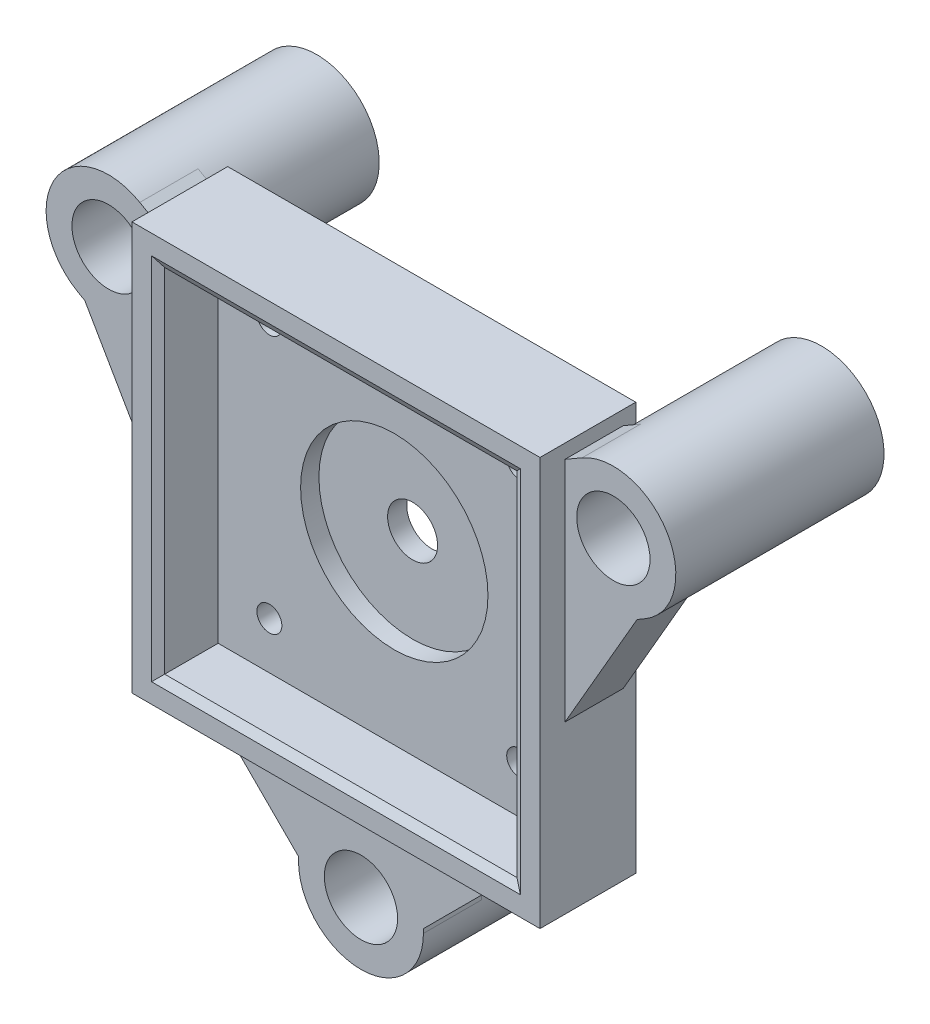
SolidWorks part; units mm, degrees
ref_plane "Ebene vorne" through (0, 0, 0) normal (0, 0, 1) x (1, 0, 0)
ref_plane "Ebene oben" through (0, 0, 0) normal (0, 1, 0) x (1, 0, 0)
ref_plane "Ebene rechts" through (0, 0, 0) normal (1, 0, 0) x (0, 0, -1)
sketch "Skizze1" plane through (0, 0, 0) normal (0, 0, 1) x (1, 0, 0)
  line L1 (-24.5, 24.5) -> (24.5, 24.5)
  line L2 (-24.5, 24.5) -> (-24.5, -24.5)
  line L3 (-24.5, -24.5) -> (24.5, -24.5)
  line L4 (24.5, 24.5) -> (24.5, -24.5)
  line L5 (-24.5, 24.5) -> (24.5, -24.5) construction
  line L6 (-24.5, -24.5) -> (24.5, 24.5) construction
  point P0 (0, 0)
  dimension "D1" = 49
  dimension "D2" = 49
extrude "Aufsatz-Linear austragen1" add sketch "Skizze1" along normal blind 11.5
sketch "Skizze2" plane through (0, 0, 11.5) normal (0, 0, 1) x (1, 0, 0)
  line L1 (-21.15, 21.15) -> (21.15, 21.15)
  line L2 (-21.15, 21.15) -> (-21.15, -21.15)
  line L3 (-21.15, -21.15) -> (21.15, -21.15)
  line L4 (21.15, 21.15) -> (21.15, -21.15)
  line L5 (-21.15, 21.15) -> (21.15, -21.15) construction
  line L6 (-21.15, -21.15) -> (21.15, 21.15) construction
  point P0 (0, 0)
  dimension "D1" = 42.3
  dimension "D2" = 42.3
extrude "Schnitt-Linear austragen1" cut sketch "Skizze2" against normal blind 5
sketch "Skizze3" plane through (0, 0, 6.5) normal (0, 0, 1) x (1, 0, 0)
  circle A0 centre (0, 0) radius 2.85
  dimension "D1" = 5.7
extrude "Schnitt-Linear austragen2" cut sketch "Skizze3" against normal blind 7
sketch "Skizze4" plane through (0, 0, 6.5) normal (0, 0, 1) x (1, 0, 0)
  circle A0 centre (0, 0) radius 35
sketch "Skizze5" plane through (0, 0, 6.5) normal (0, 0, 1) x (1, 0, 0)
  line L0 (0, -35) -> (0, 0) construction
  line L1 (-7.5, -35) -> (-7.5, 0)
  line L2 (7.5, -35) -> (7.5, 0)
  line L3 (30.3109, 17.5) -> (0, 0) construction
  line L4 (34.0609, 11.0048) -> (3.75, -6.4952)
  line L5 (26.5609, 23.9952) -> (-3.75, 6.4952)
  line L6 (-30.3109, 17.5) -> (0, 0) construction
  line L7 (-26.5609, 23.9952) -> (3.75, 6.4952)
  line L8 (-34.0609, 11.0048) -> (-3.75, -6.4952)
  circle A0 centre (0, -35) radius 7.5
  circle A1 centre (0, 0) radius 35 construction
  circle A2 centre (-30.3109, 17.5) radius 7.5
  circle A3 centre (30.3109, 17.5) radius 7.5
  arc A4 (-7.5, -35) -> (7.5, -35) centre (0, -35) ccw
  arc A5 (7.5, 0) -> (-7.5, 0) centre (0, 0) ccw
  arc A6 (34.0609, 11.0048) -> (26.5609, 23.9952) centre (30.3109, 17.5) ccw
  arc A7 (-3.75, 6.4952) -> (3.75, -6.4952) centre (0, 0) ccw
  arc A8 (-26.5609, 23.9952) -> (-34.0609, 11.0048) centre (-30.3109, 17.5) ccw
  arc A9 (-3.75, -6.4952) -> (3.75, 6.4952) centre (0, 0) ccw
  point P4 (0, -17.5)
  point P11 (0, 0)
  point P16 (15.1554, 8.75)
  point P22 (-15.1554, 8.75)
  line M5 (-21.15, -21.15) -> (21.15, -21.15)
  dimension "D1" = 15
  dimension "D3" = 7.5
  dimension "D4" = 7.5
  dimension "D5" = 7.5
  dimension "D2" = 3
extrude "Aufsatz-Linear austragen2" add sketch "Skizze5" along normal blind 2 and the other way blind 5 contours L4 A6 L5 A3 | A0 | A9 L8 L1 L2 L4 M5 | L1 A4 L2 A0 M5
sketch "Skizze6" plane through (0, 0, 11.5) normal (0, 0, 1) x (1, 0, 0)
  line L1 (-21.15, 21.15) -> (21.15, 21.15)
  line L2 (-21.15, 21.15) -> (-21.15, -21.15)
  line L3 (-21.15, -21.15) -> (21.15, -21.15)
  line L4 (21.15, 21.15) -> (21.15, -21.15)
  line L5 (-21.15, 21.15) -> (21.15, -21.15) construction
  line L6 (-21.15, -21.15) -> (21.15, 21.15) construction
  point P0 (0, 0)
extrude "Schnitt-Linear austragen3" cut sketch "Skizze6" against normal blind 7
sketch "Skizze8" plane through (0, 0, 1.5) normal (0, 0, -1) x (-1, 0, 0)
  circle A0 centre (-30.3109, 17.5) radius 7.5
  circle A3 centre (0, -35) radius 7.5
  circle A4 centre (30.3109, 17.5) radius 7.5
  dimension "D1" = 15
  dimension "D2" = 15
  dimension "D3" = 15
extrude "Aufsatz-Linear austragen3" add sketch "Skizze8" along normal blind 18
sketch "Skizze10" plane through (0, 0, -16.5) normal (0, 0, -1) x (-1, 0, 0)
  circle A0 centre (-30.3109, 17.5) radius 2.5
  circle A1 centre (30.3109, 17.5) radius 2.5
  circle A2 centre (0, -35) radius 2.5
  point P10 (0, 0)
  dimension "D1" = 3
  dimension "D2" = 5
sketch "Skizze17" plane through (0, 0, 4.5) normal (0, 0, 1) x (1, 0, 0)
  circle A0 centre (0, 0) radius 3
  dimension "D1" = 6
sketch "Skizze18" plane through (0, 0, 4.5) normal (0, 0, 1) x (1, 0, 0)
  circle A0 centre (0, 0) radius 11.25
  dimension "D1" = 22.5
chamfer "Fase2" distance 10 4 edges at (24.5, 5.4848, 5) (-24.5, 5.4848, 5) (-7.5, -24.5, 5) (7.5, -24.5, 5)
chamfer "Fase4" distance 1 angle 30 4 edges at (0, -21.15, 11.5) (-21.15, 0, 11.5) (0, 21.15, 11.5) (21.15, 0, 11.5)
extrude "Schnitt-Linear austragen8" cut sketch "Skizze17" against normal blind 23 contours A0
extrude "Schnitt-Linear austragen9" cut sketch "Skizze18" against normal blind 2.2 contours A0
extrude "Schnitt-Linear austragen10" cut sketch "Skizze10" against normal through all both and the other way through all
sketch "Skizze19" plane through (0, 0, 8.5) normal (0, 0, 1) x (1, 0, 0)
  circle A0 centre (30.3109, 17.5) radius 4.4
extrude "Schnitt-Linear austragen11" cut sketch "Skizze19" against normal blind 12 contours A0
pattern_circular "Kreismuster1" count 3 over 360 about axis through (0, 0, 0) along (0, 0, 1) of "Schnitt-Linear austragen11"
sketch "Skizze20" plane through (0, 0, 4.5) normal (0, 0, 1) x (1, 0, 0)
  line L1 (-15, 15.5) -> (15, 15.5)
  line L2 (-15, 15.5) -> (-15, -15.5)
  line L3 (-15, -15.5) -> (15, -15.5)
  line L4 (15, 15.5) -> (15, -15.5)
  line L5 (-15, 15.5) -> (15, -15.5) construction
  line L6 (-15, -15.5) -> (15, 15.5) construction
  point P0 (0, 0)
  dimension "D1" = 31
  dimension "D2" = 30
sketch "Skizze21" plane through (0, 0, 4.5) normal (0, 0, 1) x (1, 0, 0)
  circle A0 centre (-15, 15.5) radius 1.5
  circle A1 centre (15, 15.5) radius 1.5
  circle A2 centre (15, -15.5) radius 1.5
  circle A3 centre (-15, -15.5) radius 1.5
  dimension "D1" = 3
extrude "Schnitt-Linear austragen12" cut sketch "Skizze21" against normal blind 10
sketch "Skizze22" plane through (0, 0, 0) normal (0, 0, -1) x (-1, 0, 0)
  circle A0 centre (-15, 15.5) radius 3
  circle A1 centre (15, 15.5) radius 3
  circle A2 centre (15, -15.5) radius 3
  circle A3 centre (-15, -15.5) radius 3
  dimension "D1" = 6
extrude "Schnitt-Linear austragen13" cut sketch "Skizze22" against normal blind 2
